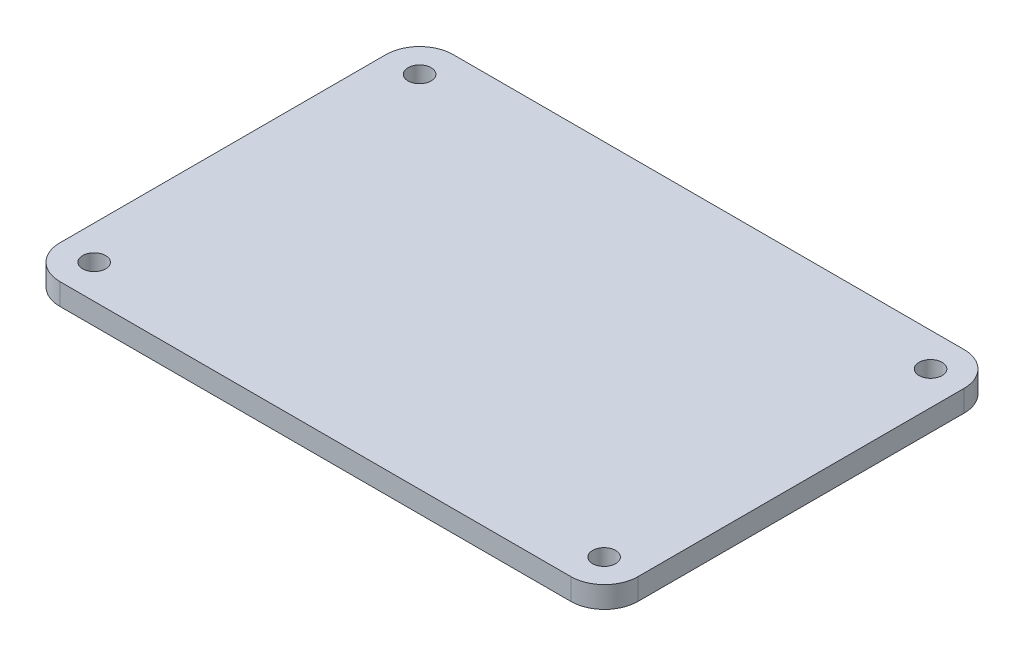
SolidWorks part; units mm, degrees
ref_plane "Front Plane" through (0, 0, 0) normal (0, 0, 1) x (1, 0, 0)
ref_plane "Top Plane" through (0, 0, 0) normal (0, 1, 0) x (1, 0, 0)
ref_plane "Right Plane" through (0, 0, 0) normal (1, 0, 0) x (0, 0, -1)
sketch "Sketch2" plane through (0, 0, 0) normal (0, 1, 0) x (1, 0, 0)
  line L0 (107.4879, 137.3364) -> (32.1345, 137.3364)
  line L1 (27.178, 142.2929) -> (27.178, 190.3801)
  line L2 (32.1345, 195.3366) -> (107.4879, 195.3366)
  line L3 (112.4444, 190.3801) -> (112.4444, 142.2929)
  circle A0 centre (32.1804, 190.3377) radius 1.7004
  circle A1 centre (32.1804, 142.3388) radius 1.7004
  circle A2 centre (107.4455, 142.2859) radius 1.7004
  circle A3 centre (107.4949, 190.3871) radius 1.7004
  spline S0 degree 3 poles (32.1345, 137.3364) (29.397, 137.3364) (27.178, 139.5554) (27.178, 142.2929) knots 1 1 1 1 2 2 2 2
  spline S1 degree 3 poles (27.178, 190.3801) (27.178, 193.1176) (29.397, 195.3366) (32.1345, 195.3366) knots 3 3 3 3 4 4 4 4
  spline S2 degree 3 poles (107.4879, 195.3366) (110.2254, 195.3366) (112.4444, 193.1176) (112.4444, 190.3801) knots 5 5 5 5 6 6 6 6
  spline S3 degree 3 poles (112.4444, 142.2929) (112.4444, 139.5554) (110.2254, 137.3364) (107.4879, 137.3364) knots 7 7 7 7 8 8 8 8
extrude "Boss-Extrude2" add sketch "Sketch2" along normal blind 3.175
